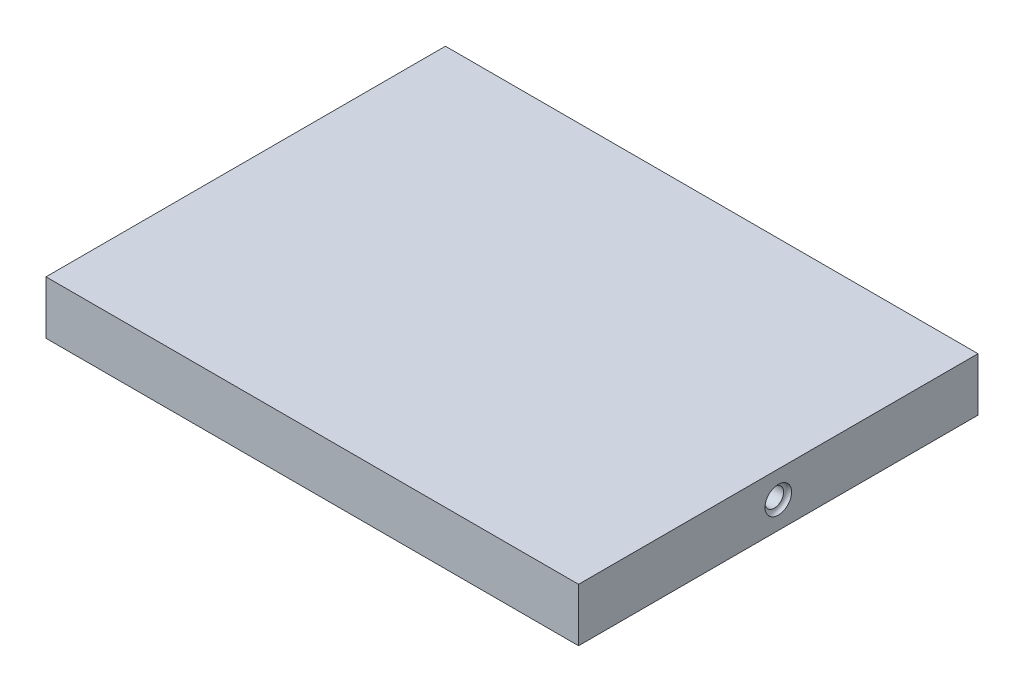
SolidWorks part; units mm, degrees
ref_plane "Front Plane" through (0, 0, 0) normal (0, 0, 1) x (1, 0, 0)
ref_plane "Top Plane" through (0, 0, 0) normal (0, 1, 0) x (1, 0, 0)
ref_plane "Right Plane" through (0, 0, 0) normal (1, 0, 0) x (0, 0, -1)
sketch "Sketch1" plane through (0, 0, 0) normal (0, 1, 0) x (1, 0, 0)
  line L1 (-10, 7.5) -> (10, 7.5)
  line L2 (-10, 7.5) -> (-10, -7.5)
  line L3 (-10, -7.5) -> (10, -7.5)
  line L4 (10, 7.5) -> (10, -7.5)
  line L5 (-10, 7.5) -> (10, -7.5) construction
  line L6 (-10, -7.5) -> (10, 7.5) construction
  point P0 (0, 0)
  dimension "D1" = 20
  dimension "D2" = 15
extrude "Boss-Extrude1" add sketch "Sketch1" along normal blind 2
sketch "Sketch2" plane through (0, 0, 0) normal (0, 0, 1) x (1, 0, 0)
  line L0 (-10, 1) -> (10, 1)
  line L1 (-10, 2) -> (-10, 0) construction
  line L2 (10, 2) -> (10, 0) construction
  line L3 (9.85, 1.35) -> (3.4, 1.35)
  line L4 (-3.4, 1.35) -> (-9.85, 1.35)
  line L5 (2.6, 1.35) -> (-2.6, 1.35)
  line L6 (-10, 1.5) -> (-10, 1)
  line L7 (10, 1.5) -> (10, 1)
  arc A0 (-10, 1.5) -> (-9.85, 1.35) centre (-10, 1.35) cw
  arc A1 (9.85, 1.35) -> (10, 1.5) centre (10, 1.35) cw
  arc A2 (-3.4, 1.35) -> (-2.6, 1.35) centre (-3, 1.35) cw
  arc A3 (2.6, 1.35) -> (3.4, 1.35) centre (3, 1.35) cw
  dimension "D2" = 0.15
  dimension "D3" = 0.15
  dimension "D6" = 0.4
  dimension "D7" = 0.4
  dimension "D1" = 0.35
  dimension "D4" = 0.15
  dimension "D5" = 0.15
  dimension "D8" = 3
  dimension "D9" = 3
revolve "Cut-Revolve1" cut sketch "Sketch2" angle 360 about L0
